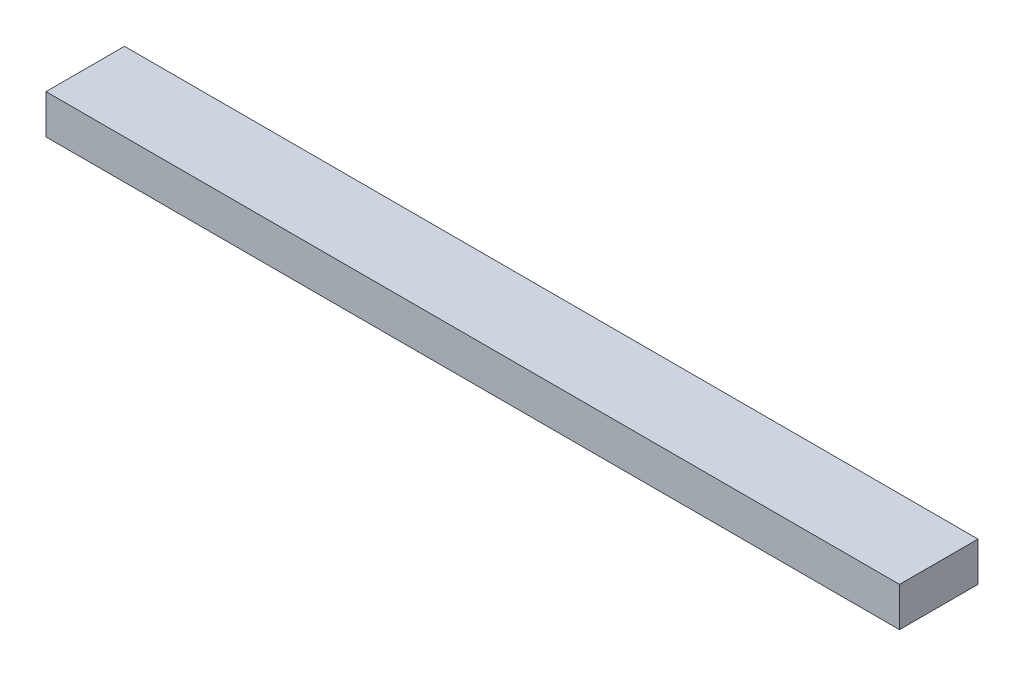
SolidWorks part; units mm, degrees
material "Acrylic (Medium-high impact)"
ref_plane "Front Plane" through (0, 0, 0) normal (0, 0, 1) x (1, 0, 0)
ref_plane "Top Plane" through (0, 0, 0) normal (0, 1, 0) x (1, 0, 0)
ref_plane "Right Plane" through (0, 0, 0) normal (1, 0, 0) x (0, 0, -1)
sketch "Sketch1" plane through (0, 0, 0) normal (0, 1, 0) x (1, 0, 0)
  line L1 (-276.225, -25.4) -> (276.225, -25.4)
  line L2 (-276.225, -25.4) -> (-276.225, 25.4)
  line L3 (-276.225, 25.4) -> (276.225, 25.4)
  line L4 (276.225, -25.4) -> (276.225, 25.4)
  line L5 (-276.225, -25.4) -> (276.225, 25.4) construction
  line L6 (-276.225, 25.4) -> (276.225, -25.4) construction
  point P0 (0, 0)
  dimension "D1" = 552.45
  dimension "D2" = 50.8
extrude "Boss-Extrude1" add sketch "Sketch1" along normal blind 25.4
